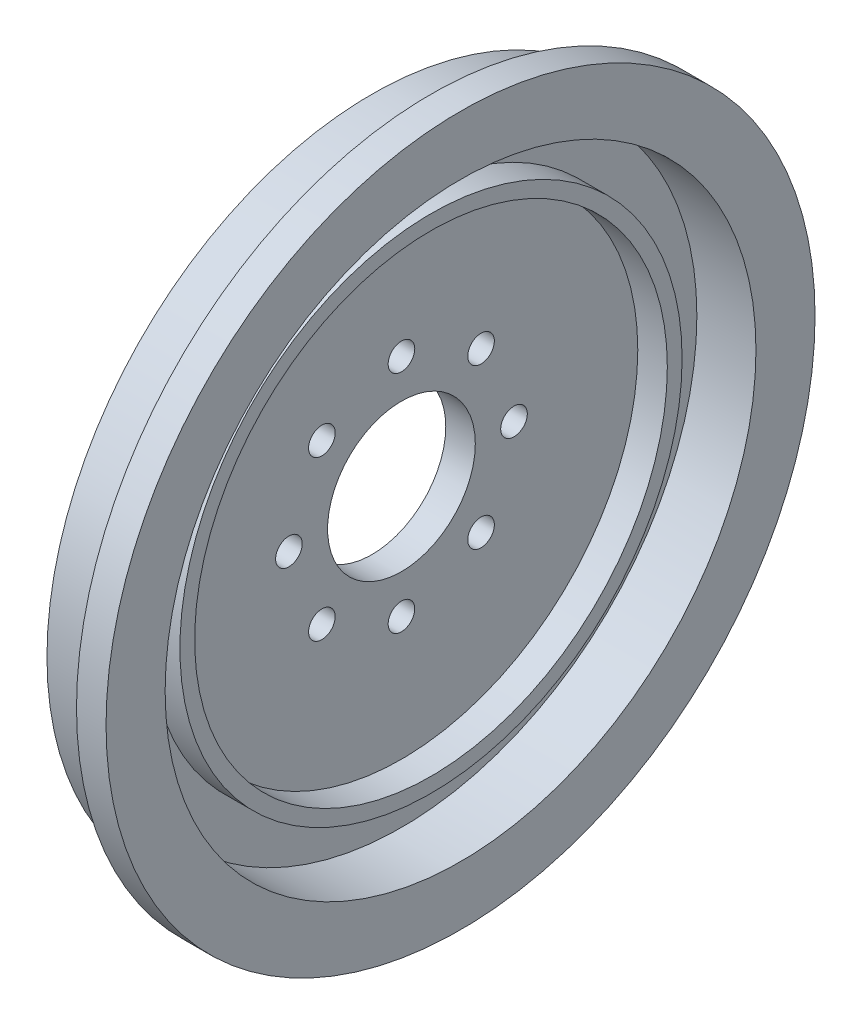
SolidWorks part; units mm, degrees
ref_plane "Płaszczyzna przednia" through (0, 0, 0) normal (0, 0, 1) x (1, 0, 0)
ref_plane "Płaszczyzna górna" through (0, 0, 0) normal (0, 1, 0) x (1, 0, 0)
ref_plane "Płaszczyzna prawa" through (0, 0, 0) normal (1, 0, 0) x (0, 0, -1)
sketch "Szkic1" plane through (0, 0, 0) normal (1, 0, 0) x (0, 0, -1)
  circle A0 centre (0, 0) radius 120
  dimension "D1" = 240
extrude "Dodanie-wyciągnięcie1" add sketch "Szkic1" along normal blind 30
sketch "Szkic2" plane through (30, 0, 0) normal (1, 0, 0) x (0, 0, -1)
  circle A0 centre (0, 0) radius 100
  dimension "D1" = 200
extrude "Wytnij-wyciągnięcie1" cut sketch "Szkic2" against normal blind 20
sketch "Szkic3" plane through (10, 0, 0) normal (1, 0, 0) x (0, 0, -1)
  circle A0 centre (0, 0) radius 38.1
  circle A1 centre (0, 38.1) radius 4.5
  circle A2 centre (0, 0) radius 38.1
  circle A3 centre (26.9408, 26.9408) radius 4.5
  circle A4 centre (0, 0) radius 38.1
  circle A5 centre (38.1, 0) radius 4.5
  circle A6 centre (0, 0) radius 38.1
  circle A7 centre (26.9408, -26.9408) radius 4.5
  circle A8 centre (0, 0) radius 38.1
  circle A9 centre (0, -38.1) radius 4.5
  circle A10 centre (0, 0) radius 38.1
  circle A11 centre (-26.9408, -26.9408) radius 4.5
  circle A12 centre (0, 0) radius 38.1
  circle A13 centre (-38.1, 0) radius 4.5
  circle A14 centre (0, 0) radius 38.1
  circle A15 centre (-26.9408, 26.9408) radius 4.5
  point P29 (0, 0)
  dimension "D1" = 76.2
  dimension "D2" = 9
  dimension "D3" = 8
extrude "Wytnij-wyciągnięcie2" cut sketch "Szkic3" against normal through all contours A14 A15 | A14 A15 | A0 A1 | A0 A1 | A4 A5 | A4 A5 | A6 A7 | A6 A7 | A8 A9 | A8 A9 | A10 A11 | A10 A11 | A12 A13 | A12 A13 | A2 A3
sketch "Szkic4" plane through (10, 0, 0) normal (1, 0, 0) x (0, 0, -1)
  circle A0 centre (0, 0) radius 25
  dimension "D1" = 50
extrude "Wytnij-wyciągnięcie3" cut sketch "Szkic4" against normal through all
sketch "Szkic5" plane through (10, 0, 0) normal (1, 0, 0) x (0, 0, -1)
  circle A0 centre (0, 0) radius 85
  circle A1 centre (0, 0) radius 80
  dimension "D1" = 170
  dimension "D2" = 160
extrude "Dodanie-wyciągnięcie2" add sketch "Szkic5" along normal blind 10 contours A0 | A1
sketch "Szkic6" plane through (30, 0, 0) normal (1, 0, 0) x (0, 0, -1)
  circle A0 centre (0, 0) radius 120
  circle A1 centre (0, 0) radius 110
  dimension "D1" = 240
  dimension "D2" = 220
extrude "Wytnij-wyciągnięcie4" cut sketch "Szkic6" against normal blind 20 from offset 10
